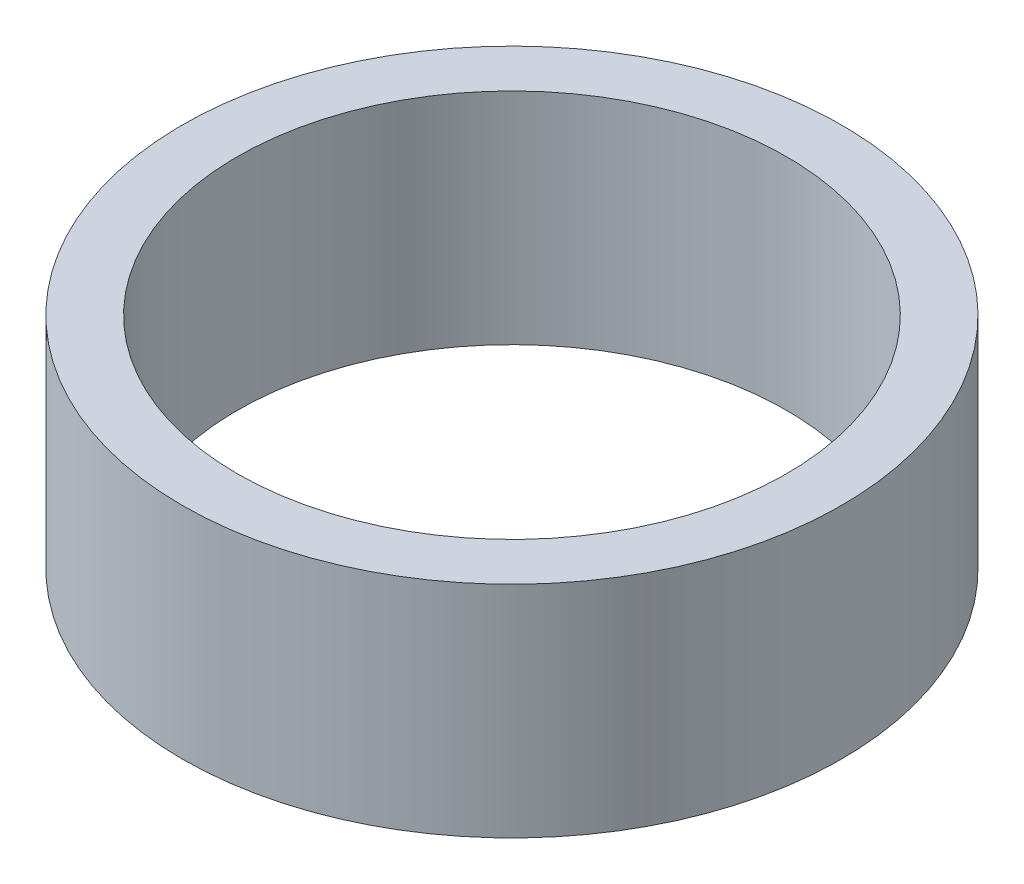
SolidWorks part; units mm, degrees
ref_plane "Front Plane" through (0, 0, 0) normal (0, 0, 1) x (1, 0, 0)
ref_plane "Top Plane" through (0, 0, 0) normal (0, 1, 0) x (1, 0, 0)
ref_plane "Right Plane" through (0, 0, 0) normal (1, 0, 0) x (0, 0, -1)
sketch "Sketch1" plane through (0, 0, 0) normal (0, 1, 0) x (1, 0, 0)
  circle A0 centre (0, 0) radius 0.635
  circle A1 centre (0, 0) radius 0.762
  dimension "D1" = 1.27
  dimension "D2" = 1.524
extrude "Boss-Extrude1" add sketch "Sketch1" along normal blind 0.508
